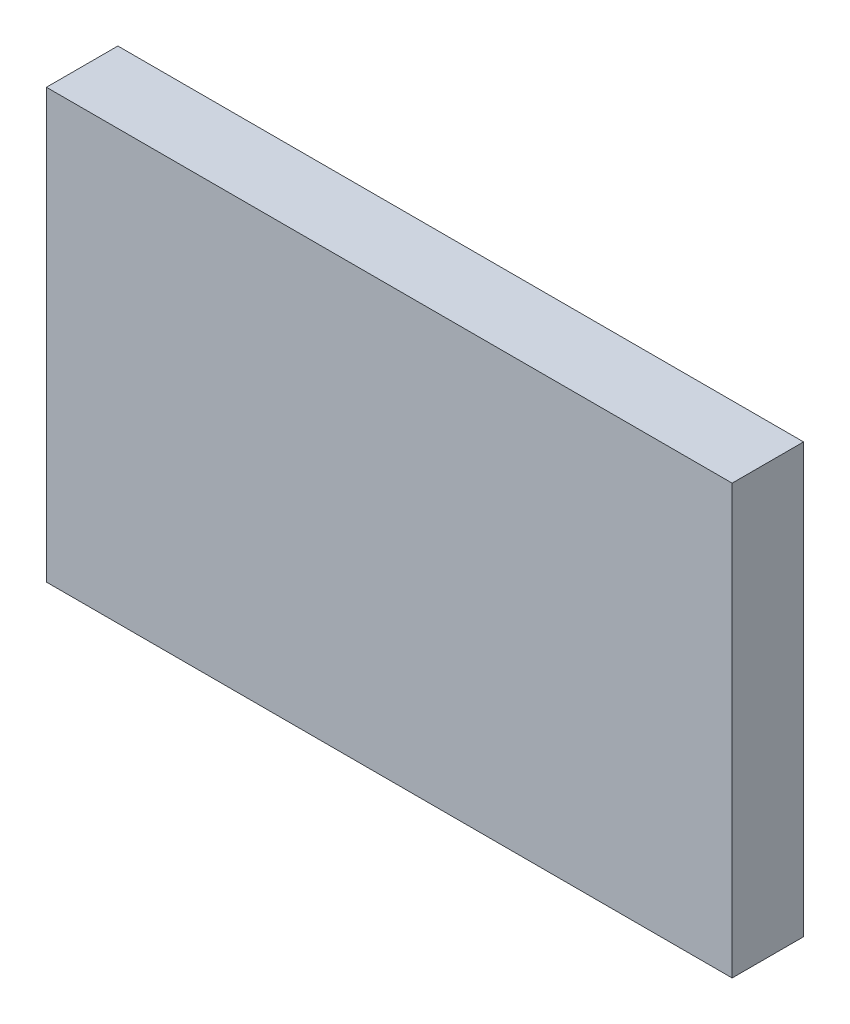
SolidWorks part; units mm, degrees
ref_plane "Front Plane" through (0, 0, 0) normal (0, 0, 1) x (1, 0, 0)
ref_plane "Top Plane" through (0, 0, 0) normal (0, 1, 0) x (1, 0, 0)
ref_plane "Right Plane" through (0, 0, 0) normal (1, 0, 0) x (0, 0, -1)
sketch "Sketch1" plane through (0, 0, 0) normal (0, 0, 1) x (1, 0, 0)
  line L1 (-24, 15) -> (24, 15)
  line L2 (-24, 15) -> (-24, -15)
  line L3 (-24, -15) -> (24, -15)
  line L4 (24, 15) -> (24, -15)
  line L5 (-24, 15) -> (24, -15) construction
  line L6 (-24, -15) -> (24, 15) construction
  point P0 (0, 0)
  dimension "D1" = 48
  dimension "D2" = 30
extrude "Boss-Extrude1" add sketch "Sketch1" along normal blind 5
